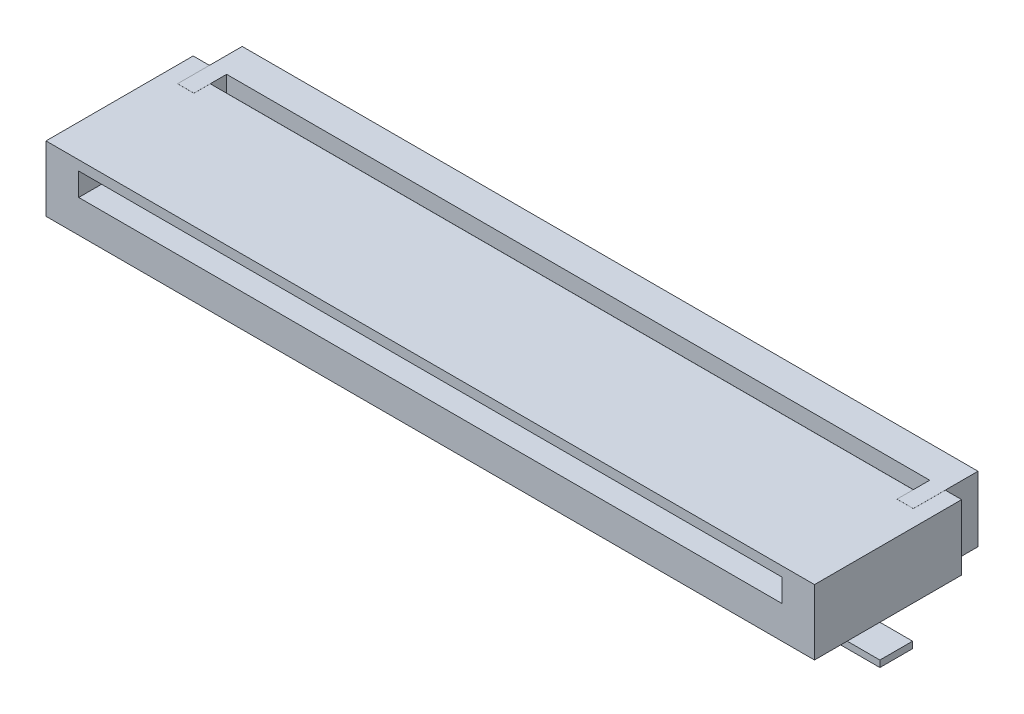
SolidWorks part; units mm, degrees
ref_plane "前视基准面" through (0, 0, 0) normal (0, 0, 1) x (1, 0, 0)
ref_plane "上视基准面" through (0, 0, 0) normal (0, 1, 0) x (1, 0, 0)
ref_plane "右视基准面" through (0, 0, 0) normal (1, 0, 0) x (0, 0, -1)
sketch "草图1" plane through (0, 0, 0) normal (0, 1, 0) x (1, 0, 0)
  line L1 (-11.75, -2.75) -> (11.75, -2.75)
  line L2 (-11.75, -2.75) -> (-11.75, 2.75)
  line L3 (-11.75, 2.75) -> (11.75, 2.75)
  line L4 (11.75, -2.75) -> (11.75, 2.75)
  line L5 (-11.75, -2.75) -> (11.75, 2.75) construction
  line L6 (-11.75, 2.75) -> (11.75, -2.75) construction
  point P0 (0, 0)
  dimension "D1" = 23.5
  dimension "D2" = 5.5
extrude "凸台-拉伸1" add sketch "草图1" along normal blind 2
sketch "草图2" plane through (0, 2, 0) normal (0, 1, 0) x (1, 0, 0)
  line L0 (0, -6.1376) -> (0, 6.1376) construction
  line L1 (-11.75, 2.75) -> (-11.25, 2.75)
  line L2 (-11.75, 2.75) -> (-11.75, 1.75)
  line L3 (-11.75, 1.75) -> (-11.25, 1.75)
  line L4 (-11.25, 2.75) -> (-11.25, 1.75)
  line L5 (11.25, 2.75) -> (11.25, 1.75)
  line L6 (11.75, 1.75) -> (11.25, 1.75)
  line L7 (11.75, 2.75) -> (11.75, 1.75)
  line L8 (11.75, 2.75) -> (11.25, 2.75)
  point P9 (0, 0)
  dimension "D1" = 1
  dimension "D2" = 0.5
extrude "切除-拉伸1" cut sketch "草图2" against normal through all
sketch "草图4" plane through (0, 0, 0) normal (0, -1, 0) x (1, 0, 0)
  line L0 (-11.75, -1.75) -> (-11.75, 2.75) construction
  line L1 (-12.75, 1.75) -> (-10.75, 1.75)
  line L2 (-12.75, 1.75) -> (-12.75, 0.75)
  line L3 (-12.75, 0.75) -> (-10.75, 0.75)
  line L4 (-10.75, 1.75) -> (-10.75, 0.75)
  line L5 (-11.75, 2.75) -> (11.75, 2.75) construction
  line L6 (0, 0) -> (0, 7.0534) construction
  line L7 (10.75, 1.75) -> (10.75, 0.75)
  line L8 (12.75, 0.75) -> (10.75, 0.75)
  line L9 (12.75, 1.75) -> (12.75, 0.75)
  line L10 (12.75, 1.75) -> (10.75, 1.75)
  dimension "D1" = 1
  dimension "D2" = 2
  dimension "D3" = 1
  dimension "D4" = 1
extrude "凸台-拉伸2" add sketch "草图4" along normal blind 0.2
sketch "草图5" plane through (0, 0, 0) normal (0, -1, 0) x (1, 0, 0)
  line L0 (11.25, -2.75) -> (11.25, -1.75) construction
  line L1 (10.75, -2.55) -> (-10.75, -2.55)
  line L2 (10.75, -2.55) -> (10.75, -2.35)
  line L3 (10.75, -2.35) -> (-10.75, -2.35)
  line L4 (-10.75, -2.55) -> (-10.75, -2.35)
  line L5 (-11.25, -1.75) -> (-11.25, -2.75) construction
  line L6 (11.25, -2.75) -> (-11.25, -2.75) construction
  dimension "D1" = 0.5
  dimension "D2" = 0.5
  dimension "D3" = 0.2
  dimension "D4" = 0.2
extrude "凸台-拉伸3" add sketch "草图5" along normal blind 0.3
sketch "草图6" plane through (0, 0, 2.75) normal (0, 0, 1) x (1, 0, 0)
  line L0 (-11.75, 2) -> (11.75, 2) construction
  line L1 (-10.75, 1.7) -> (10.75, 1.7)
  line L2 (-10.75, 1.7) -> (-10.75, 1)
  line L3 (-10.75, 1) -> (10.75, 1)
  line L4 (10.75, 1.7) -> (10.75, 1)
  line L5 (-11.75, 2) -> (-11.75, 0) construction
  line L6 (11.75, 2) -> (11.75, 0) construction
  dimension "D1" = 0.3
  dimension "D2" = 1
  dimension "D3" = 1
  dimension "D4" = 0.7
extrude "切除-拉伸2" cut sketch "草图6" against normal blind 4.5
sketch "草图7" plane through (0, 2, 0) normal (0, 1, 0) x (1, 0, 0)
  line L0 (-11.25, 1.75) -> (-11.25, 0.7733)
  line L1 (-11.25, 0.7733) -> (-10.75, 0.7733)
  line L2 (-10.75, 0.7733) -> (-10.75, 1.2733)
  line L3 (-10.75, 1.2733) -> (10.75, 1.2733)
  line L4 (-11.25, 1.75) -> (-11.75, 1.75)
  line L5 (-11.75, 1.75) -> (-11.75, -2.75)
  line L6 (-11.75, -2.75) -> (11.75, -2.75)
  line L7 (-11.75, -2.75) -> (11.75, -2.75) construction
  line L8 (0, 0) -> (0, 7.5114) construction
  line L9 (11.75, 1.75) -> (11.75, -2.75)
  line L10 (11.25, 1.75) -> (11.75, 1.75)
  line L11 (10.75, 0.7733) -> (10.75, 1.2733)
  line L12 (11.25, 0.7733) -> (10.75, 0.7733)
  line L13 (11.25, 1.75) -> (11.25, 0.7733)
  point P19 (0, -2.75)
  point P22 (0, 1.2733)
  dimension "D1" = 0.5
  dimension "D2" = 0.5
extrude "切除-拉伸3" cut sketch "草图7" against normal blind 0.002
sketch "草图8" plane through (0, 2, 0) normal (0, 1, 0) x (1, 0, 0)
  line L0 (10.75, 0.7733) -> (10.75, 1.2733) construction
  line L1 (-10.75, 1.2733) -> (10.75, 1.2733)
  line L2 (-10.75, 1.2733) -> (-10.75, 1.7733)
  line L3 (-10.75, 1.7733) -> (10.75, 1.7733)
  line L4 (10.75, 1.2733) -> (10.75, 1.7733)
  line L5 (-10.75, 1.2733) -> (-10.75, 0.7733) construction
  dimension "D1" = 0.5
extrude "切除-拉伸4" cut sketch "草图8" against normal blind 0.5
